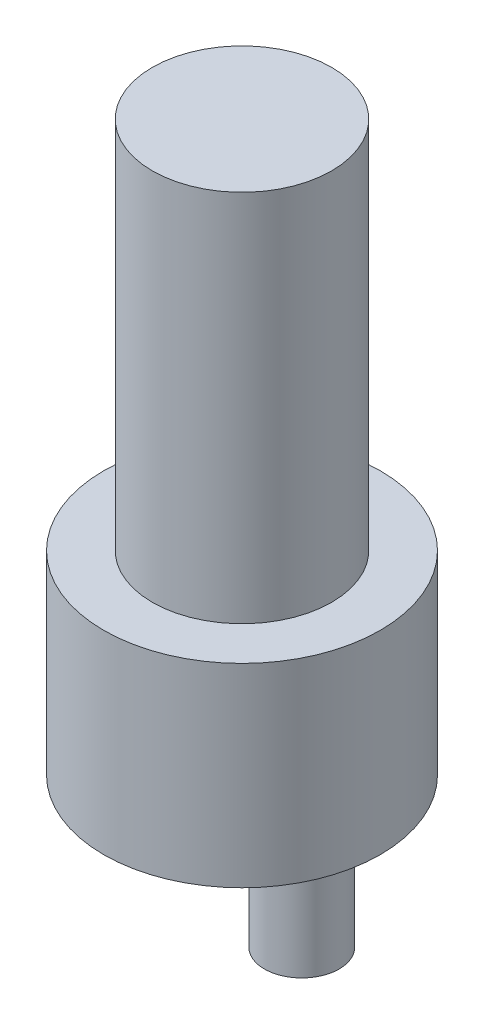
SolidWorks part; units mm, degrees
ref_plane "Plano frontal" through (0, 0, 0) normal (0, 0, 1) x (1, 0, 0)
ref_plane "Plano superior" through (0, 0, 0) normal (0, 1, 0) x (1, 0, 0)
ref_plane "Plano direito" through (0, 0, 0) normal (1, 0, 0) x (0, 0, -1)
sketch "Esboço1" plane through (0, 0, 0) normal (0, 1, 0) x (1, 0, 0)
  circle A0 centre (0, 0) radius 18.5
  dimension "D1" = 37
extrude "Ressalto-extrusão1" add sketch "Esboço1" along normal blind 100
sketch "Esboço2" plane through (0, 100, 0) normal (0, 1, 0) x (1, 0, 0)
  circle A0 centre (0, 0) radius 12
  circle A1 centre (0, 0) radius 18.5
  dimension "D1" = 24
extrude "Corte-extrusão1" cut sketch "Esboço2" against normal blind 50 contours A0 | A1
sketch "Esboço3" plane through (0, 0, 0) normal (0, -1, 0) x (-1, 0, 0)
  circle A0 centre (0, 0) radius 18.5
  circle A1 centre (0, 8) radius 5
  dimension "D1" = 10
  dimension "D2" = 8
extrude "Corte-extrusão2" cut sketch "Esboço3" against normal blind 24
